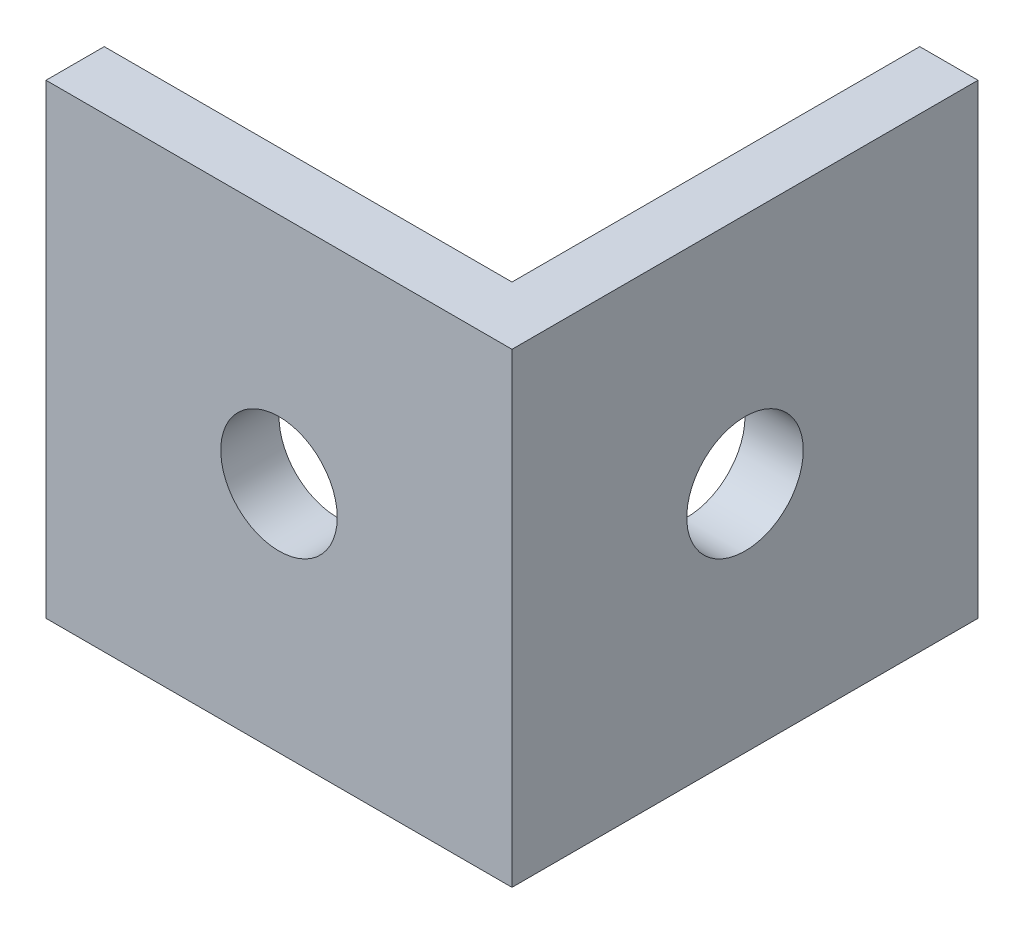
SolidWorks part; units mm, degrees
ref_plane "Front Plane" through (0, 0, 0) normal (0, 0, 1) x (1, 0, 0)
ref_plane "Top Plane" through (0, 0, 0) normal (0, 1, 0) x (1, 0, 0)
ref_plane "Right Plane" through (0, 0, 0) normal (1, 0, 0) x (0, 0, -1)
sketch "Sketch1" plane through (0, 0, 0) normal (0, 1, 0) x (1, 0, 0)
  line L0 (0, 0) -> (25.4, 0)
  line L1 (25.4, 0) -> (25.4, 25.4)
  line L2 (25.4, 25.4) -> (22.225, 25.4)
  line L3 (22.225, 25.4) -> (22.225, 3.175)
  line L4 (22.225, 3.175) -> (0, 3.175)
  line L5 (0, 3.175) -> (0, 0)
  dimension "D1" = 3.175
  dimension "D2" = 3.175
  dimension "D3" = 25.4
  dimension "D4" = 25.4
extrude "Boss-Extrude1" add sketch "Sketch1" along normal blind 25.4
sketch "Sketch2" plane through (25.4, 0, 0) normal (1, 0, 0) x (0, 0, -1)
  line L0 (25.4, 25.4) -> (25.4, 0) construction
  line L1 (0, 25.4) -> (25.4, 25.4) construction
  circle A0 centre (12.7, 12.7) radius 3.175
  dimension "D3" = 6.35
  dimension "D1" = 12.7
  dimension "D2" = 12.7
extrude "Cut-Extrude1" cut sketch "Sketch2" against normal blind 25.4
sketch "Sketch3" plane through (0, 0, 0) normal (0, 0, 1) x (1, 0, 0)
  line L0 (0, 25.4) -> (0, 0) construction
  line L1 (0, 0) -> (25.4, 0) construction
  circle A0 centre (12.7, 12.7) radius 3.175
  dimension "D3" = 6.35
  dimension "D1" = 12.7
  dimension "D2" = 12.7
extrude "Cut-Extrude2" cut sketch "Sketch3" against normal blind 25.4
